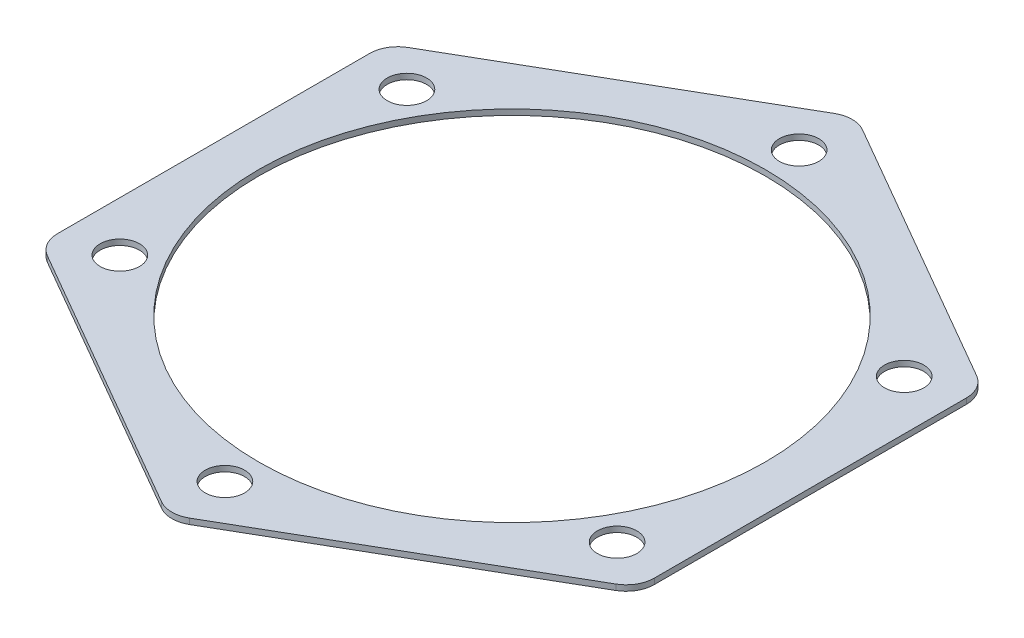
SolidWorks part; units mm, degrees
ref_plane "Front Plane" through (0, 0, 0) normal (0, 0, 1) x (1, 0, 0)
ref_plane "Top Plane" through (0, 0, 0) normal (0, 1, 0) x (1, 0, 0)
ref_plane "Right Plane" through (0, 0, 0) normal (1, 0, 0) x (0, 0, -1)
sketch "Sketch1" plane through (0, 0, 0) normal (0, 1, 0) x (1, 0, 0)
  line L1 (53, -27.7128) -> (53, 27.7128)
  line L2 (50.5, 32.0429) -> (2.5, 59.7558)
  line L3 (-2.5, 59.7558) -> (-50.5, 32.0429)
  line L4 (-53, 27.7128) -> (-53, -27.7128)
  line L5 (-50.5, -32.0429) -> (-2.5, -59.7558)
  line L6 (2.5, -59.7558) -> (50.5, -32.0429)
  circle A0 centre (0, 0) radius 53 construction
  circle A2 centre (0, 0) radius 45
  arc A3 (-2.5, -59.7558) -> (2.5, -59.7558) centre (0, -55.4256) ccw
  arc A4 (53, -27.7128) -> (50.5, -32.0429) centre (48, -27.7128) cw
  arc A5 (53, 27.7128) -> (50.5, 32.0429) centre (48, 27.7128) ccw
  arc A6 (2.5, 59.7558) -> (-2.5, 59.7558) centre (0, 55.4256) ccw
  arc A7 (-50.5, 32.0429) -> (-53, 27.7128) centre (-48, 27.7128) ccw
  arc A8 (-53, -27.7128) -> (-50.5, -32.0429) centre (-48, -27.7128) ccw
  circle A9 centre (0, 0) radius 51 construction
  circle A10 centre (0, 51) radius 3.5
  circle A11 centre (44.1673, 25.5) radius 3.5
  circle A12 centre (44.1673, -25.5) radius 3.5
  circle A13 centre (0, -51) radius 3.5
  circle A14 centre (-44.1673, -25.5) radius 3.5
  circle A15 centre (-44.1673, 25.5) radius 3.5
  point P37 (0, 0)
  dimension "D2" = 5
  dimension "D3" = 6
  dimension "D1" = 106
extrude "Boss-Extrude2" add sketch "Sketch1" along normal blind 1
